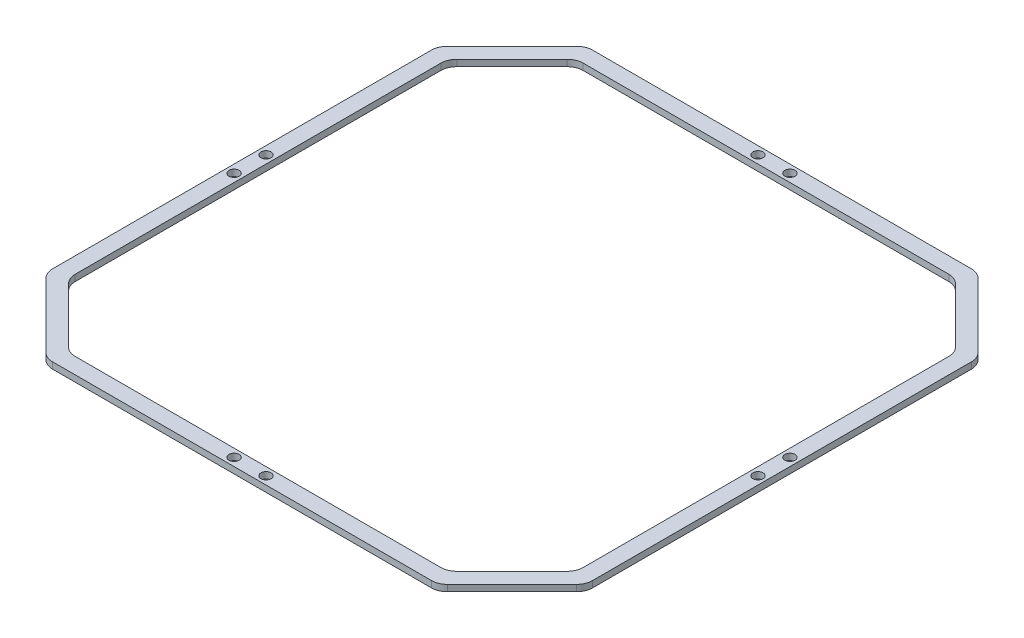
SolidWorks part; units mm, degrees
ref_plane "前视基准面" through (0, 0, 0) normal (0, 0, 1) x (1, 0, 0)
ref_plane "上视基准面" through (0, 0, 0) normal (0, 1, 0) x (1, 0, 0)
ref_plane "右视基准面" through (0, 0, 0) normal (1, 0, 0) x (0, 0, -1)
other "Configuration Table"
sketch "草图1" plane through (0, 0, 0) normal (0, 1, 0) x (1, 0, 0)
  line L0 (0, 0) -> (0, 48.4864) construction
  line L1 (-45, -45) -> (45, -45) construction
  line L2 (-45, -45) -> (-45, 45) construction
  line L3 (-45, 45) -> (45, 45) construction
  line L4 (45, -45) -> (45, 45) construction
  line L5 (-45, -45) -> (45, 45) construction
  line L6 (-45, 45) -> (45, -45) construction
  line L7 (-43.5, -25) -> (43.5, -25) construction
  line L8 (-43.5, -25) -> (-43.5, 25) construction
  line L9 (-43.5, 25) -> (43.5, 25) construction
  line L10 (43.5, -25) -> (43.5, 25) construction
  line L11 (-43.5, -25) -> (43.5, 25) construction
  line L12 (-43.5, 25) -> (43.5, -25) construction
  line L13 (-10, -10) -> (10, -10) construction
  line L14 (-10, -10) -> (-10, 10) construction
  line L15 (-10, 10) -> (10, 10) construction
  line L16 (10, -10) -> (10, 10) construction
  line L17 (-10, -10) -> (10, 10) construction
  line L18 (-10, 10) -> (10, -10) construction
  line L19 (-5, 82) -> (5, 82) construction
  line L20 (0, 82) -> (60.3259, 82) construction
  line L21 (60.3259, 82) -> (82, 60.3259) construction
  line L22 (82, 60.3259) -> (82, 0) construction
  line L23 (0, 79.5) -> (57.2193, 79.5)
  line L24 (60.7548, 78.0355) -> (78.0355, 60.7548)
  line L25 (79.5, 57.2193) -> (79.5, 0)
  line L26 (0, 84.5) -> (59.2904, 84.5)
  line L27 (62.8259, 83.0355) -> (83.0355, 62.8259)
  line L28 (84.5, 59.2904) -> (84.5, 0)
  line L29 (82, 5) -> (82, -5) construction
  line L30 (84.5, 0) -> (84.5, -59.2904)
  line L31 (83.0355, -62.8259) -> (62.8259, -83.0355)
  line L32 (59.2904, -84.5) -> (0, -84.5)
  line L33 (0, -84.5) -> (-59.2904, -84.5)
  line L34 (-62.8259, -83.0355) -> (-83.0355, -62.8259)
  line L35 (-84.5, -59.2904) -> (-84.5, -1.7805)
  line L36 (-84.5, -1.7805) -> (-84.5, 59.2904)
  line L37 (-83.0355, 62.8259) -> (-62.8259, 83.0355)
  line L38 (-59.2904, 84.5) -> (0, 84.5)
  line L39 (79.5, 0) -> (79.5, -57.2193)
  line L40 (78.0355, -60.7548) -> (60.7548, -78.0355)
  line L41 (57.2193, -79.5) -> (0, -79.5)
  line L42 (0, -79.5) -> (-57.2193, -79.5)
  line L43 (-60.7548, -78.0355) -> (-78.0355, -60.7548)
  line L44 (-79.5, -57.2193) -> (-79.5, -1.1654)
  line L45 (-79.5, -1.1654) -> (-79.5, 57.2193)
  line L46 (-78.0355, 60.7548) -> (-60.7548, 78.0355)
  line L47 (-57.2193, 79.5) -> (0, 79.5)
  line L48 (61.3614, 84.5) -> (84.5, 61.3614) construction
  line L49 (84.5, 61.3614) -> (84.5, 0) construction
  line L50 (0, 84.5) -> (61.3614, 84.5) construction
  line L51 (59.2904, 79.5) -> (79.5, 59.2904) construction
  line L52 (79.5, 59.2904) -> (79.5, 0) construction
  line L53 (0, 79.5) -> (59.2904, 79.5) construction
  circle A0 centre (45, 45) radius 31.5 construction
  circle A1 centre (-45, 45) radius 31.5 construction
  circle A2 centre (-45, -45) radius 31.5 construction
  circle A3 centre (45, -45) radius 31.5 construction
  circle A4 centre (-45, 45) radius 9.5 construction
  circle A5 centre (45, 45) radius 9.5 construction
  circle A6 centre (45, -45) radius 9.5 construction
  circle A7 centre (-45, -45) radius 9.5 construction
  circle A8 centre (-39.5, 21) radius 1.6 construction
  circle A9 centre (39.5, 21) radius 1.6 construction
  circle A10 centre (39.5, -21) radius 1.6 construction
  circle A11 centre (-39.5, -21) radius 1.6 construction
  circle A12 centre (-10, 10) radius 1.6 construction
  circle A13 centre (10, 10) radius 1.6 construction
  circle A14 centre (-10, -10) radius 1.6 construction
  circle A15 centre (10, -10) radius 1.6 construction
  circle A16 centre (5, 82) radius 1.6
  circle A17 centre (-5, 82) radius 1.6
  circle A18 centre (82, 5) radius 1.6
  circle A19 centre (82, -5) radius 1.6
  circle A20 centre (5, -82) radius 1.6
  circle A21 centre (-5, -82) radius 1.6
  circle A22 centre (-82, -5) radius 1.6
  circle A23 centre (-82, 5) radius 1.6
  arc A24 (-84.5, 59.2904) -> (-83.0355, 62.8259) centre (-79.5, 59.2904) cw
  arc A25 (-83.0355, -62.8259) -> (-84.5, -59.2904) centre (-79.5, -59.2904) cw
  arc A26 (-59.2904, -84.5) -> (-62.8259, -83.0355) centre (-59.2904, -79.5) cw
  arc A27 (62.8259, -83.0355) -> (59.2904, -84.5) centre (59.2904, -79.5) cw
  arc A28 (84.5, -59.2904) -> (83.0355, -62.8259) centre (79.5, -59.2904) cw
  arc A29 (83.0355, 62.8259) -> (84.5, 59.2904) centre (79.5, 59.2904) cw
  arc A30 (59.2904, 84.5) -> (62.8259, 83.0355) centre (59.2904, 79.5) cw
  arc A31 (-62.8259, 83.0355) -> (-59.2904, 84.5) centre (-59.2904, 79.5) cw
  arc A32 (-79.5, 57.2193) -> (-78.0355, 60.7548) centre (-74.5, 57.2193) cw
  arc A33 (-78.0355, -60.7548) -> (-79.5, -57.2193) centre (-74.5, -57.2193) cw
  arc A34 (-57.2193, -79.5) -> (-60.7548, -78.0355) centre (-57.2193, -74.5) cw
  arc A35 (60.7548, -78.0355) -> (57.2193, -79.5) centre (57.2193, -74.5) cw
  arc A36 (79.5, -57.2193) -> (78.0355, -60.7548) centre (74.5, -57.2193) cw
  arc A37 (78.0355, 60.7548) -> (79.5, 57.2193) centre (74.5, 57.2193) cw
  arc A38 (57.2193, 79.5) -> (60.7548, 78.0355) centre (57.2193, 74.5) cw
  arc A39 (-60.7548, 78.0355) -> (-57.2193, 79.5) centre (-57.2193, 74.5) cw
  point P0 (0, 0)
  point P19 (0, 0)
  point P32 (0, 0)
  point P62 (0, 0)
  point P88 (0, 0)
  point P97 (0, 0)
  point P126 (0, 0)
  point P127 (0, 0)
  dimension "D3" = 63
  dimension "D4" = 63
  dimension "D5" = 63
  dimension "D6" = 63
  dimension "D7" = 19
  dimension "D8" = 19
  dimension "D9" = 19
  dimension "D10" = 19
  dimension "D15" = 3.2
  dimension "D18" = 3.2
  dimension "D21" = 3.2
  dimension "D24" = 3.2
  dimension "D27" = 3.2
  dimension "D28" = 3.2
  dimension "D29" = 3.2
  dimension "D30" = 3.2
  dimension "D34" = 3.2
  dimension "D35" = 3.2
  dimension "D42" = 5
  dimension "D1" = 90
  dimension "D2" = 90
  dimension "D11" = 87
  dimension "D12" = 50
  dimension "D13" = 4
  dimension "D14" = 4
  dimension "D16" = 4
  dimension "D17" = 4
  dimension "D19" = 4
  dimension "D20" = 4
  dimension "D22" = 4
  dimension "D23" = 4
  dimension "D25" = 20
  dimension "D26" = 20
  dimension "D31" = 5
  dimension "D32" = 5
  dimension "D33" = 82
  dimension "D39" = 37
  dimension "D37" = 2.5
  dimension "D38" = 2.5
  dimension "D36" = 4
  dimension "D40" = 4
  dimension "D41" = 4
extrude "凸台-拉伸1" add sketch "草图1" along normal blind 2
